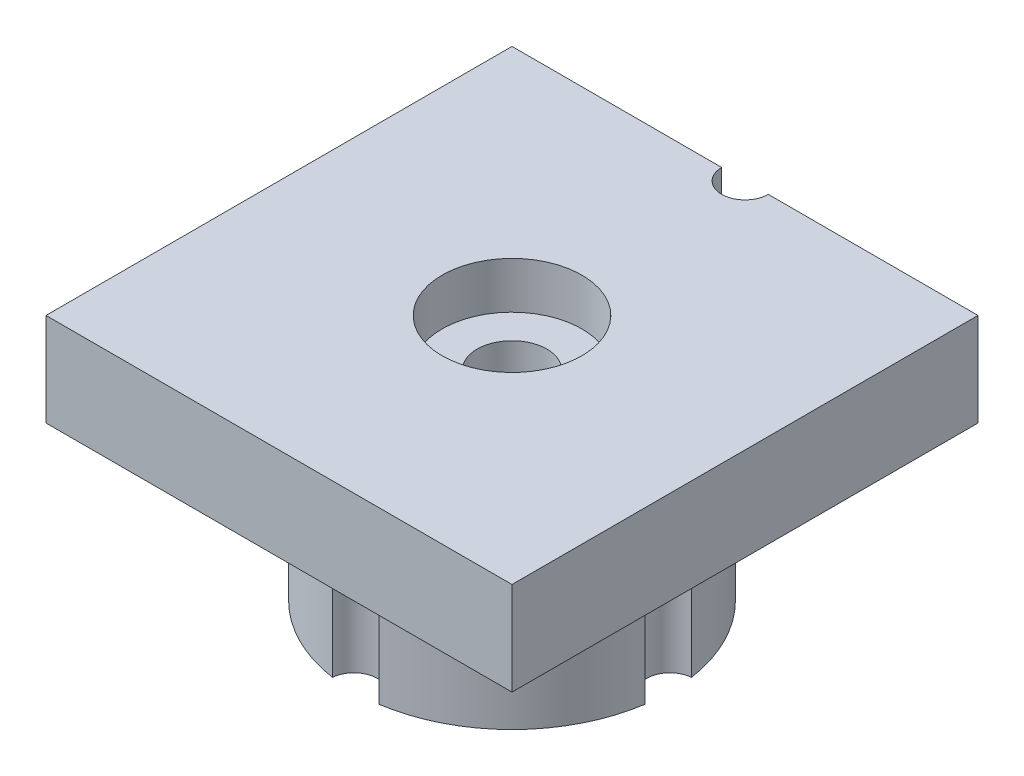
SolidWorks part; units mm, degrees
ref_plane "前视基准面" through (0, 0, 0) normal (0, 0, 1) x (1, 0, 0)
ref_plane "上视基准面" through (0, 0, 0) normal (0, 1, 0) x (1, 0, 0)
ref_plane "右视基准面" through (0, 0, 0) normal (1, 0, 0) x (0, 0, -1)
other "Configuration Table"
sketch "草图1" plane through (0, 0, 0) normal (0, 1, 0) x (1, 0, 0)
  line L1 (-5, -5) -> (5, -5)
  line L2 (-5, -5) -> (-5, 5)
  line L3 (-5, 5) -> (5, 5)
  line L4 (5, -5) -> (5, 5)
  line L5 (-5, -5) -> (5, 5) construction
  line L6 (-5, 5) -> (5, -5) construction
  point P0 (0, 0)
  dimension "D1" = 10
  dimension "D2" = 10
extrude "凸台-拉伸1" add sketch "草图1" along normal blind 2
sketch "草图2" plane through (0, 0, 0) normal (0, -1, 0) x (1, 0, 0)
  line L0 (0, 0) -> (-3.39, 0) construction
  arc A0 (-3.3531, -0.4986) -> (-0.4986, -3.3531) centre (0, 0) ccw
  arc A1 (-3.3531, -0.4986) -> (-3.3531, 0.4986) centre (-3.39, 0) ccw
  arc A2 (-0.4986, 3.3531) -> (0.4986, 3.3531) centre (0, 3.39) ccw
  arc A3 (3.3531, 0.4986) -> (3.3531, -0.4986) centre (3.39, 0) ccw
  arc A4 (0.4986, -3.3531) -> (-0.4986, -3.3531) centre (0, -3.39) ccw
  arc A5 (0.4986, -3.3531) -> (3.3531, -0.4986) centre (0, 0) ccw
  arc A6 (3.3531, 0.4986) -> (0.4986, 3.3531) centre (0, 0) ccw
  arc A7 (-0.4986, 3.3531) -> (-3.3531, 0.4986) centre (0, 0) ccw
  point P17 (0, 0)
  dimension "D1" = 6.78
  dimension "D2" = 1
  dimension "D3" = 4
extrude "凸台-拉伸2" add sketch "草图2" along normal blind 3.3
sketch "草图3" plane through (0, -3.3, 0) normal (0, -1, 0) x (1, 0, 0)
  circle A0 centre (0, 0) radius 2
  dimension "D1" = 4
extrude "切除-拉伸1" cut sketch "草图3" against normal blind 3.3
sketch "草图4" plane through (0, 0, 0) normal (0, -1, 0) x (1, 0, 0)
  circle A0 centre (0, 0) radius 0.75
  dimension "D1" = 1.5
extrude "切除-拉伸2" cut sketch "草图4" against normal blind 3.3 contours A0
sketch "草图5" plane through (0, 2, 0) normal (0, 1, 0) x (1, 0, 0)
  circle A0 centre (0, 0) radius 1.5
  dimension "D1" = 3
extrude "切除-拉伸3" cut sketch "草图5" against normal blind 1
sketch "草图6" plane through (0, 2, 0) normal (0, 1, 0) x (1, 0, 0)
  line L0 (5, 5) -> (-5, 5) construction
  line L1 (-0.5, 5) -> (0.5, 5)
  arc A0 (-0.5, 5) -> (0.5, 5) centre (0, 5) ccw
  dimension "D1" = 1
extrude "切除-拉伸4" cut sketch "草图6" against normal through all
